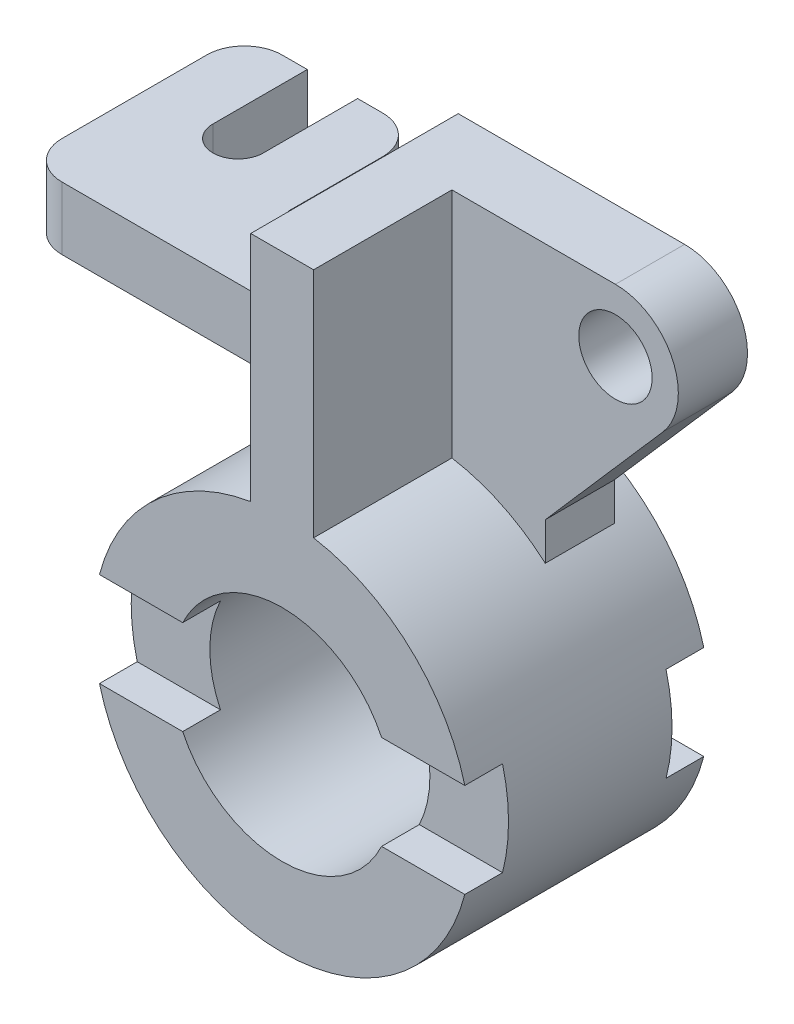
SolidWorks part; units mm, degrees
material "1060 Alloy"
ref_plane "Front Plane" through (0, 0, 0) normal (0, 0, 1) x (1, 0, 0)
ref_plane "Top Plane" through (0, 0, 0) normal (0, 1, 0) x (1, 0, 0)
ref_plane "Right Plane" through (0, 0, 0) normal (1, 0, 0) x (0, 0, -1)
sketch "Sketch1" plane through (0, 0, 0) normal (0, 0, 1) x (1, 0, 0)
  circle A0 centre (0, 0) radius 30
  circle A1 centre (0, 0) radius 17.5
  dimension "D1" = 60
  dimension "D2" = 35
extrude "Boss-Extrude1" add sketch "Sketch1" along normal blind 38
sketch "Sketch2" plane through (0, 0, 38) normal (0, 0, 1) x (1, 0, 0)
  line L0 (-30, 0) -> (30, 0)
  line L1 (0, 0) -> (0, 72.9331)
  circle A0 centre (0, 0) radius 30 construction
ref_plane "Plane1" through (0, 0, 38) normal (0, 0, 1) x (1, 0, 0)
sketch "Sketch3" plane through (0, 0, 38) normal (0, 0, 1) x (1, 0, 0)
  line L2 (5, 29.5804) -> (5, 66.5)
  line L3 (-5, 29.5804) -> (-5, 66.5)
  line L4 (-5, 66.5) -> (5, 66.5)
  line L5 (0, 30) -> (0, 66.5) construction
  arc A0 (5, 29.5804) -> (-5, 29.5804) centre (0, 0) ccw
  point P6 (0, 29.5804)
  dimension "D1" = 36.5
  dimension "D2" = 10
extrude "Boss-Extrude2" add sketch "Sketch3" against normal blind 33 contours L3 L4 L2 A0
sketch "Sketch6" plane through (5, 0, 0) normal (1, 0, 0) x (0, 0, -1)
  line L0 (-5, 66.5) -> (-38, 66.5) construction
  line L1 (-5, 29.5804) -> (-16, 29.5804)
  line L2 (-5, 29.5804) -> (-5, 66.5)
  line L3 (-5, 66.5) -> (-16, 66.5)
  line L4 (-16, 29.5804) -> (-16, 66.5)
  dimension "D1" = 11
extrude "Boss-Extrude3" add sketch "Sketch6" along normal blind 41.84 contours L2 L1 L4 L3
sketch "Sketch8" plane through (0, 0, 16) normal (0, 0, 1) x (1, 0, 0)
  line L3 (46.84, 66.5) -> (5, 66.5) construction
  line L5 (19.8431, 28.5) -> (19.8431, 22.5)
  line L6 (19.8431, 28.5) -> (38.5354, 49.926)
  line L7 (31, 66.5) -> (32.0802, 77.0303)
  line L8 (32.0802, 77.0303) -> (58.3163, 73.1703)
  line L9 (58.3163, 73.1703) -> (50.7308, 21.6131)
  line L10 (50.7308, 21.6131) -> (19.8431, 22.5)
  circle A1 centre (31, 56.5) radius 10
  circle A2 centre (31, 56.5) radius 5.835
  arc A5 (-5, 29.5804) -> (5, 29.5804) centre (0, 0) ccw construction
  dimension "D2" = 20
  dimension "D3" = 11.67
  dimension "D4" = 6
  dimension "D5" = 28
extrude "Cut-Extrude2" cut sketch "Sketch8" against normal blind 41.84
sketch "Sketch10" plane through (0, 0, 5) normal (0, 0, -1) x (-1, 0, 0)
  line L4 (-38.5354, 49.926) -> (-20.7857, 29.5804)
  line L5 (-20.7857, 29.5804) -> (-5, 29.5804)
  line L6 (5, 29.5804) -> (5, 66.5)
  line L7 (5, 66.5) -> (-31, 66.5)
  line L8 (-38.5354, 49.926) -> (-20.7857, 29.5804)
  line L9 (-20.7857, 29.5804) -> (-5, 29.5804)
  line L10 (5, 29.5804) -> (5, 66.5)
  line L11 (5, 66.5) -> (-31, 66.5)
  arc A2 (-31, 66.5) -> (-38.5354, 49.926) centre (-31, 56.5) ccw
  arc A3 (5, 29.5804) -> (-5, 29.5804) centre (0, 0) ccw
  arc A4 (-31, 66.5) -> (-38.5354, 49.926) centre (-31, 56.5) ccw
  arc A5 (5, 29.5804) -> (-5, 29.5804) centre (0, 0) ccw
  dimension "D1" = 0
sketch "Sketch11" plane through (0, 0, 5) normal (0, 0, -1) x (-1, 0, 0)
  line L0 (-19.8431, 22.5) -> (-19.8431, 28.5)
  line L1 (-19.8431, 28.5) -> (-20.7857, 29.5804)
  line L2 (-20.7857, 29.5804) -> (-5, 29.5804)
  arc A0 (-5, 29.5804) -> (-19.8431, 22.5) centre (0, 0) ccw
extrude "Boss-Extrude4" add sketch "Sketch11" against normal blind 11 contours A0 L0 L1 L2
sketch "Sketch13" plane through (-5, 0, 0) normal (-1, 0, 0) x (0, 0, 1)
  line L1 (5, 29.5804) -> (19, 29.5804)
  line L2 (5, 29.5804) -> (5, 39.5804)
  line L3 (5, 39.5804) -> (19, 39.5804)
  line L4 (19, 29.5804) -> (19, 39.5804)
  dimension "D1" = 14
  dimension "D2" = 10
extrude "Boss-Extrude7" add sketch "Sketch13" along normal blind 55 contours L2 L1 L4 L3
sketch "Sketch14" plane through (0, 39.5804, 0) normal (0, 1, 0) x (1, 0, 0)
  line L0 (-60, -5) -> (-5, -5) construction
  line L1 (-5, -19) -> (-10, -19)
  line L2 (-5, -19) -> (-5, -5)
  line L3 (-5, -5) -> (-10, -5)
  line L4 (-10, -19) -> (-10, -5)
  dimension "D1" = 5
extrude "Cut-Extrude3" cut sketch "Sketch14" against normal blind 2
sketch "Sketch15" plane through (0, 39.5804, 0) normal (0, 1, 0) x (1, 0, 0)
  line L0 (-60, -19) -> (-32, -19)
  line L1 (-60, -19) -> (-10, -19) construction
  line L2 (-60, -19) -> (-46, -19)
  line L3 (-60, -19) -> (-60, 10)
  line L4 (-32, -19) -> (-32, 10)
  line L5 (-54, 16) -> (-38, 16)
  line L6 (-46, 16) -> (-46, 1) construction
  line L7 (-42, 16) -> (-42, 1)
  line L8 (-50, 16) -> (-50, 1)
  line L9 (-60, -5) -> (-32, -5)
  line L10 (-60, -5) -> (-10, -5) construction
  arc A0 (-42, 16) -> (-50, 16) centre (-46, 16) ccw
  arc A1 (-50, 1) -> (-42, 1) centre (-46, 1) ccw
  arc A2 (-32, 10) -> (-38, 16) centre (-38, 10) ccw
  arc A3 (-54, 16) -> (-60, 10) centre (-54, 10) ccw
  point P10 (-46, 8.5)
  point P19 (-60, 16)
  line M12 (-10, -5) -> (-60, -5)
  dimension "D5" = 4
  dimension "D6" = 6
  dimension "D1" = 28
  dimension "D2" = 14
  dimension "D3" = 35
  dimension "D4" = 15
extrude "Boss-Extrude8" add sketch "Sketch15" against normal blind 10 contours L5 A3 L3 L4 A2 L7 A1 L8 M12
sketch "Sketch16" plane through (0, 39.5804, 0) normal (0, 1, 0) x (1, 0, 0)
  line L0 (-60, -4.5) -> (-60, -13)
  line L1 (-60, 10) -> (-60, -19) construction
  line L2 (-54, -19) -> (-46.6063, -19)
  line L3 (-60, -19) -> (-10, -19) construction
  line L4 (-60, -13) -> (-61.9994, -21.1408)
  line L5 (-61.9994, -21.1408) -> (-52.1026, -23.5715)
  line L6 (-52.1026, -23.5715) -> (-54, -19)
  arc A0 (-54, -19) -> (-60, -13) centre (-54, -13) cw
  point P10 (-60, -19)
  line M11 (-60, 10) -> (-60, -19)
  line M12 (-60, -19) -> (-10, -19)
  dimension "D1" = 6
extrude "Cut-Extrude4" cut sketch "Sketch16" against normal through all contours A0 M12 M11
sketch "Sketch18" plane through (0, 0, 0) normal (0, 0, -1) x (-1, 0, 0)
  line L0 (0, 0) -> (-45.9663, 0) construction
  line L1 (0, 0) -> (0, 25.66) construction
  line L2 (-10.199, -7.5) -> (-10.199, 7.5)
  line L3 (-10.199, 7.5) -> (-37.2824, 7.5)
  line L4 (-37.2824, 7.5) -> (-37.2824, -7.5)
  line L5 (-10.199, -7.5) -> (-37.2824, -7.5)
  line L6 (37.2824, 7.5) -> (37.2824, -7.5)
  line L7 (10.199, -7.5) -> (37.2824, -7.5)
  line L8 (10.199, -7.5) -> (10.199, 7.5)
  line L9 (10.199, 7.5) -> (37.2824, 7.5)
  point P6 (-43.5427, 0)
  point P9 (-10.199, 0)
  dimension "D1" = 15
extrude "Cut-Extrude5" cut sketch "Sketch18" against normal blind 6 contours L6 L7 L8 L9 | L3 L4 L5 L2
sketch "Sketch20" plane through (-5, 0, 0) normal (-1, 0, 0) x (0, 0, 1)
  line L0 (0, 26.1322) -> (38, 26.1322) construction
  line L1 (0, 30) -> (0, 7.5) construction
  line L2 (38, -30) -> (38, 29.5804) construction
  line L3 (19, 26.1322) -> (19, 60.9088)
ref_plane "Plane3" through (0, 0, 19) normal (0, 0, 1) x (0, 1, 0)
mirror "Mirror1" about plane through (0, 0, 19) normal (0, 0, 1) of "Cut-Extrude5"
